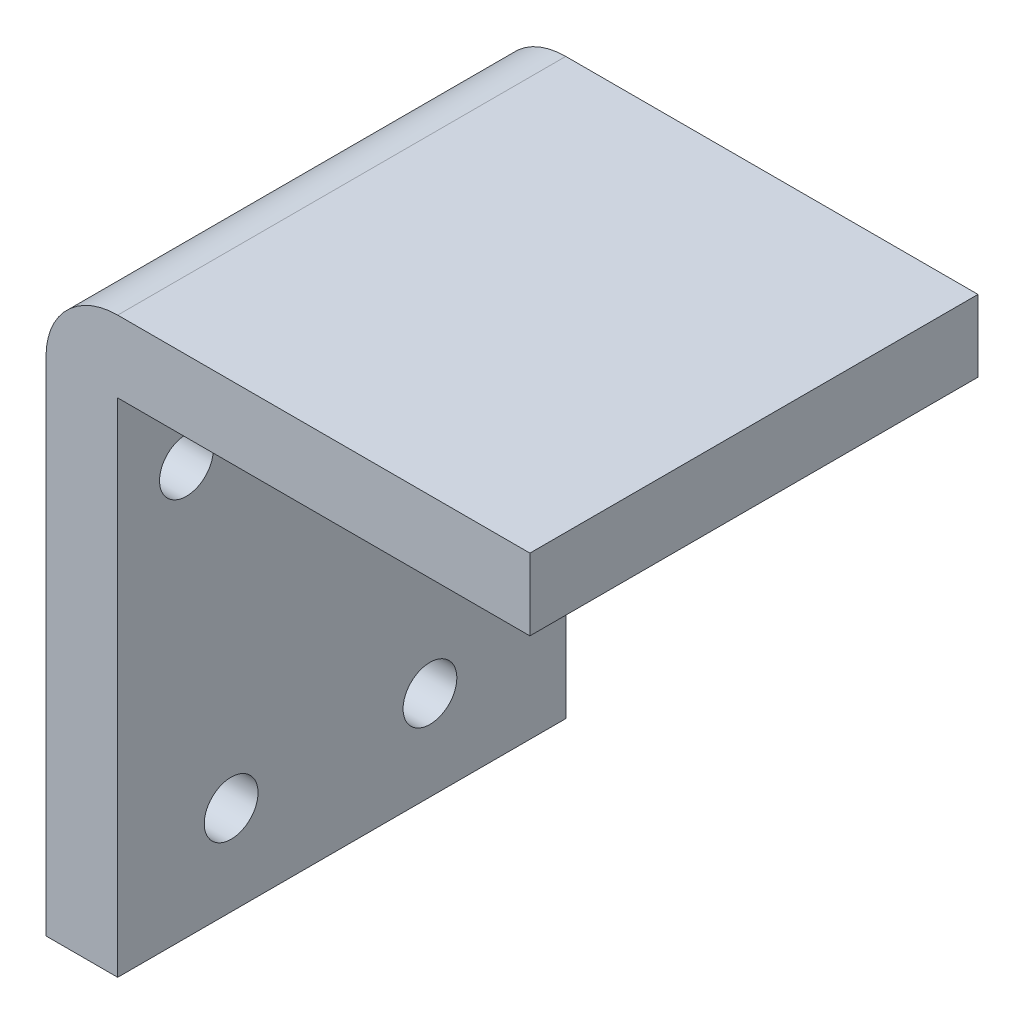
SolidWorks part; units mm, degrees
ref_plane "Alzado" through (0, 0, 0) normal (0, 0, 1) x (1, 0, 0)
ref_plane "Planta" through (0, 0, 0) normal (0, 1, 0) x (1, 0, 0)
ref_plane "Vista lateral" through (0, 0, 0) normal (1, 0, 0) x (0, 0, -1)
sketch "Croquis1" plane through (0, 0, 0) normal (0, 0, 1) x (1, 0, 0)
  line L0 (8, 0) -> (100, 0)
  line L1 (0, -8) -> (0, -120)
  line L2 (8, -8) -> (8, -120)
  line L3 (8, -8) -> (100, -8)
  line L4 (-8, -8) -> (-8, -120)
  line L5 (8, 8) -> (100, 8)
  line L6 (100, -8) -> (100, 8)
  line L7 (8, -120) -> (-8, -120)
  arc A0 (8, 0) -> (0, -8) centre (8, -8) ccw
  arc A1 (8, -8) -> (8, -8) centre (8, -8) ccw
  arc A2 (8, 8) -> (-8, -8) centre (8, -8) ccw
  point P6 (0, 0)
  dimension "D1" = 8
  dimension "D2" = 8
  dimension "D3" = 8
extrude "Saliente-Extruir1" add sketch "Croquis1" along normal blind 100 contours L5 L6 L3 A1 L2 L7 L4 A2
sketch "Croquis2" plane through (8, 0, 0) normal (1, 0, 0) x (0, 0, -1)
  circle A0 centre (-84.6662, -28.6831) radius 6
  circle A1 centre (-48.336, -28.6831) radius 6
  circle A2 centre (-15.3338, -28.6831) radius 6
  circle A3 centre (-74.6823, -99.9567) radius 6
  circle A4 centre (-30.3096, -99.9567) radius 6
extrude "Cortar-Extruir1" cut sketch "Croquis2" against normal blind 100
